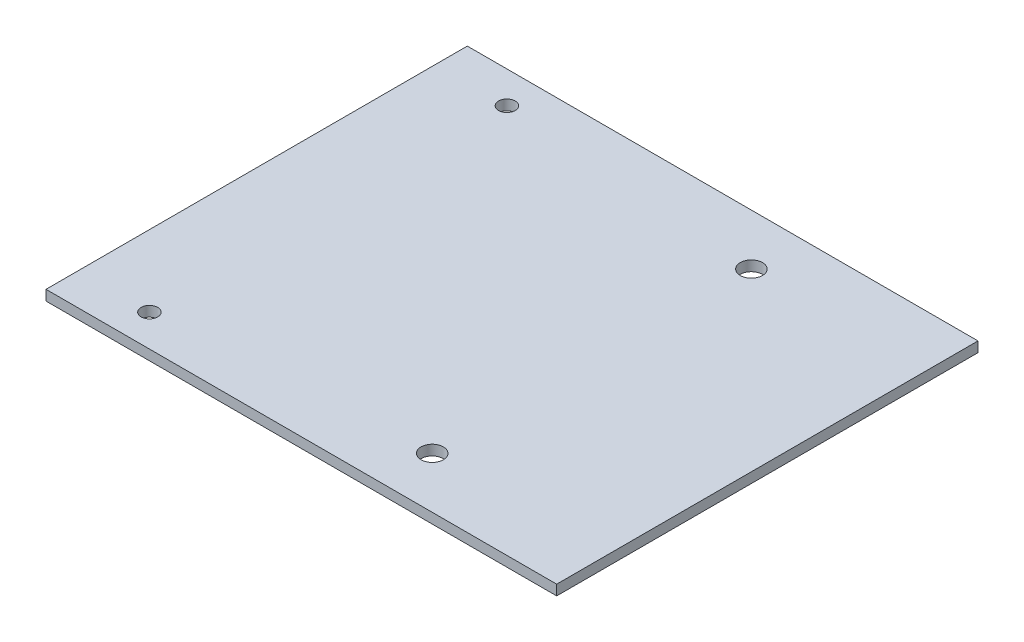
SolidWorks part; units mm, degrees
ref_plane "Front Plane" through (0, 0, 0) normal (0, 0, 1) x (1, 0, 0)
ref_plane "Top Plane" through (0, 0, 0) normal (0, 1, 0) x (1, 0, 0)
ref_plane "Right Plane" through (0, 0, 0) normal (1, 0, 0) x (0, 0, -1)
sketch "Sketch1" plane through (0, 0, 0) normal (0, 1, 0) x (1, 0, 0)
  line L1 (-40, -33) -> (40, -33)
  line L2 (-40, -33) -> (-40, 33)
  line L3 (-40, 33) -> (40, 33)
  line L4 (40, -33) -> (40, 33)
  line L5 (-40, -33) -> (40, 33) construction
  line L6 (-40, 33) -> (40, -33) construction
  point P0 (0, 0)
  dimension "D1" = 80
  dimension "D2" = 66
extrude "Boss-Extrude1" add sketch "Sketch1" along normal blind 1.6
sketch "Sketch2" plane through (0, 1.6, 0) normal (0, 1, 0) x (1, 0, 0)
  line L0 (-40, 33) -> (-40, -33) construction
  circle A4 centre (-28.802, 28) radius 1.3
  circle A5 centre (-28.802, -28) radius 1.3
  circle A6 centre (-11.1, 28) radius 3 construction
  circle A7 centre (-11.1, -28) radius 3 construction
  dimension "D1" = 2.6
  dimension "D4" = 2.6
  dimension "D5" = 56
  dimension "D6" = 28.9
  dimension "D7" = 6
  dimension "D8" = 56
  dimension "D9" = 28
  dimension "D2" = 11.198
  dimension "D3" = 11.198
extrude "Cut-Extrude1" cut sketch "Sketch2" against normal blind 1.6
sketch "Sketch4" plane through (0, 1.6, 0) normal (0, 1, 0) x (1, 0, 0)
  line L0 (40, -33) -> (40, 33) construction
  line L1 (-40, -33) -> (40, -33) construction
  line L2 (40, 33) -> (-40, 33) construction
  circle A0 centre (12.5, 25) radius 1.75
  circle A1 centre (12.5, -25) radius 1.75
  dimension "D1" = 3.5
  dimension "D2" = 3.5
  dimension "D3" = 27.5
  dimension "D4" = 27.5
  dimension "D5" = 8
  dimension "D6" = 8
extrude "Cut-Extrude2" cut sketch "Sketch4" against normal up to next
